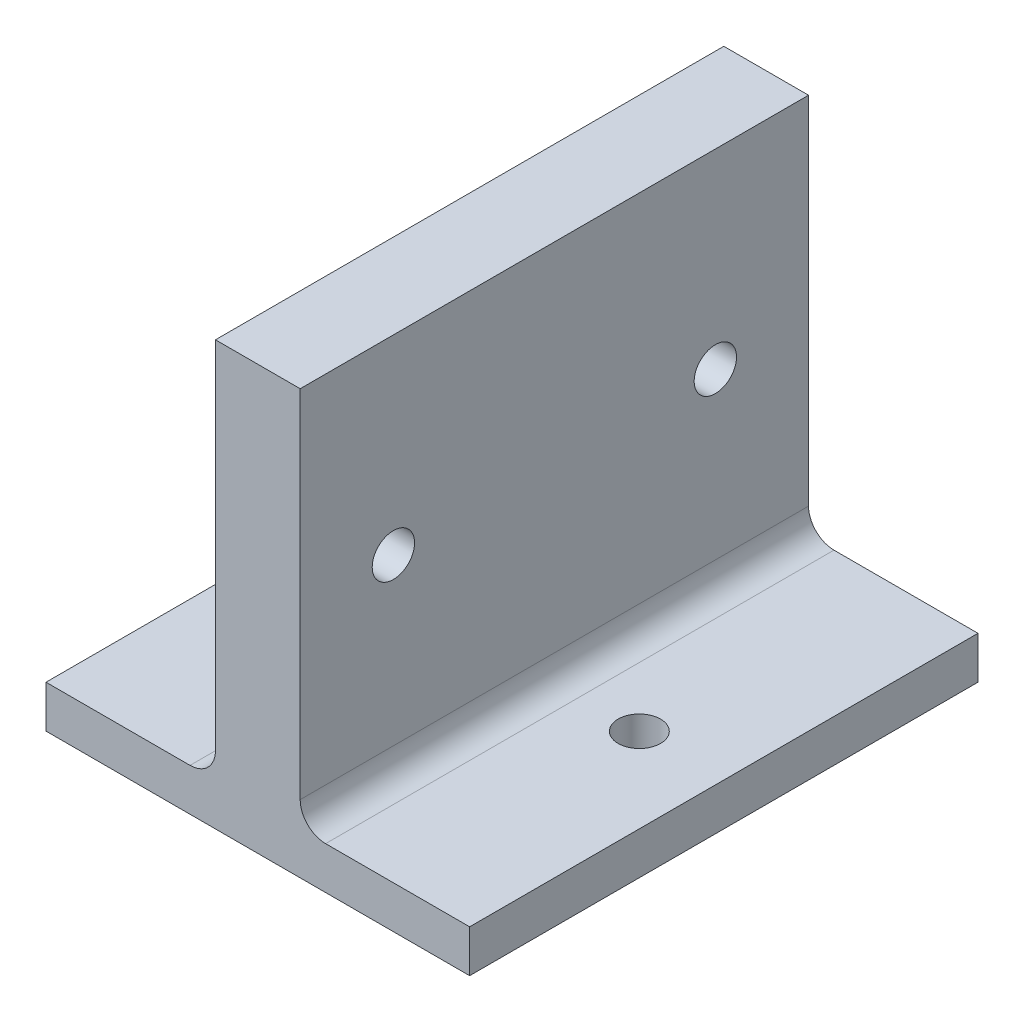
SolidWorks part; units mm, degrees
ref_plane "前视基准面" through (0, 0, 0) normal (0, 0, 1) x (1, 0, 0)
ref_plane "上视基准面" through (0, 0, 0) normal (0, 1, 0) x (1, 0, 0)
ref_plane "右视基准面" through (0, 0, 0) normal (1, 0, 0) x (0, 0, -1)
other "Configuration Table"
sketch "Sketch1" plane through (0, 0, 0) normal (0, 1, 0) x (1, 0, 0)
  line L1 (-25, 30) -> (25, 30)
  line L2 (-25, 30) -> (-25, -30)
  line L3 (-25, -30) -> (25, -30)
  line L4 (25, 30) -> (25, -30)
  line L5 (-25, 30) -> (25, -30) construction
  line L6 (-25, -30) -> (25, 30) construction
  point P0 (0, 0)
extrude "Boss-Extrude1" add sketch "Sketch1" along normal blind 5
sketch "Sketch2" plane through (0, 5, 0) normal (0, 1, 0) x (1, 0, 0)
  line L0 (-25, -30) -> (25, -30) construction
  line L1 (-5, 30) -> (5, 30)
  line L2 (-5, 30) -> (-5, -30)
  line L3 (-5, -30) -> (5, -30)
  line L4 (5, 30) -> (5, -30)
  line L5 (-5, 30) -> (5, -30) construction
  line L6 (-5, -30) -> (5, 30) construction
  point P0 (0, 0)
extrude "Boss-Extrude2" add sketch "Sketch2" along normal blind 45
sketch "Sketch3" plane through (0, 5, 0) normal (0, 1, 0) x (1, 0, 0)
  circle A0 centre (-15.0283, 0) radius 2.5
  circle A1 centre (15.0283, 0) radius 2.5
extrude "Cut-Extrude1" cut sketch "Sketch3" against normal through all
sketch "Sketch5" plane through (-5, 0, 0) normal (-1, 0, 0) x (0, 0, 1)
  line L0 (-30, 27.5) -> (-19, 27.5) construction
  line L7 (-30, 50) -> (-30, 5) construction
  line L9 (30, 27.5) -> (19, 27.5) construction
  line L10 (30, 50) -> (30, 5) construction
  circle A0 centre (-19, 27.5) radius 2.5
  circle A1 centre (19, 27.5) radius 2.5
extrude "Cut-Extrude2" cut sketch "Sketch5" against normal up to next
fillet "Fillet1" radius 3 2 edges at (5, 5, 0) (-5, 5, 0)
